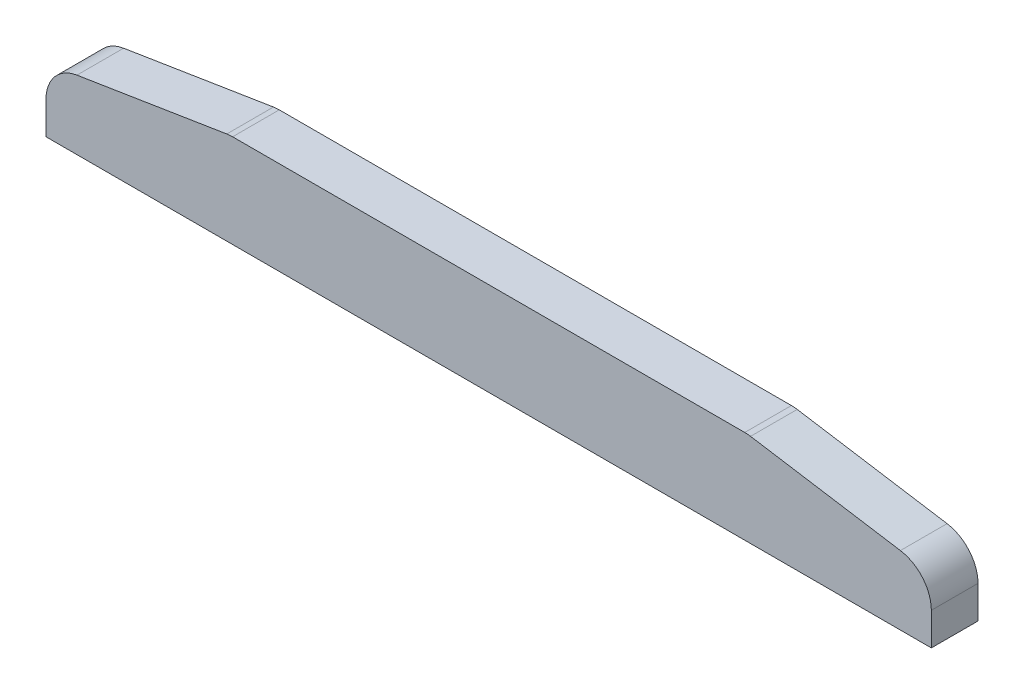
SolidWorks part; units mm, degrees
ref_plane "Front Plane" through (0, 0, 0) normal (0, 0, 1) x (1, 0, 0)
ref_plane "Top Plane" through (0, 0, 0) normal (0, 1, 0) x (1, 0, 0)
ref_plane "Right Plane" through (0, 0, 0) normal (1, 0, 0) x (0, 0, -1)
sketch "Sketch1" plane through (0, 0, 0) normal (0, 1, 0) x (1, 0, 0)
  line L1 (-120.5, -6.35) -> (120.5, -6.35)
  line L2 (-120.5, -6.35) -> (-120.5, 6.35)
  line L3 (-120.5, 6.35) -> (120.5, 6.35)
  line L4 (120.5, -6.35) -> (120.5, 6.35)
  line L5 (0, 6.35) -> (0, -6.35) construction
  line L6 (-120.5, 0) -> (120.5, 0) construction
  circle A0 centre (-112.5, 0) radius 2.1 construction
  circle A1 centre (-67.5, 0) radius 2.1 construction
  circle A2 centre (-22.5, 0) radius 2.1 construction
  circle A3 centre (22.5, 0) radius 2.1 construction
  circle A4 centre (67.5, 0) radius 2.1 construction
  circle A5 centre (112.5, 0) radius 2.1 construction
  point P0 (0, 0)
  dimension "D1" = 12.7
  dimension "D2" = 4.2
  dimension "D3" = 8
  dimension "D5" = 45
  dimension "D6" = 8
  dimension "D4" = 6
extrude "Boss-Extrude1" add sketch "Sketch1" along normal blind 25.4
chamfer "Chamfer1" distance 8 distance2 50 2 edges at (120.5, 25.4, 0) (-120.5, 25.4, 0)
hole_wizard "M5x0.8 Tapped Hole1" positions "Sketch2" profile "Sketch3" tap size "M5x0.8" standard "ANSI Metric"
sketch "Sketch2" plane through (0, 0, 0) normal (0, -1, 0) x (-1, 0, 0)
  point P15 (112.5, 0)
  point P18 (67.5, 0)
  point P21 (22.5, 0)
  point P24 (-22.5, 0)
  point P27 (-67.5, 0)
  point P30 (-112.5, 0)
sketch "Sketch3" plane through (-112.5, 0, 0) normal (1, 0, 0) x (0, 0, -1)
  line L0 (0, 0) -> (0, 13.2618)
  line L1 (0, 13.2618) -> (2.1, 12)
  line L2 (2.1, 12) -> (2.1, 0)
  line L5 (2.1, 0) -> (0, 0)
  line L10 (0, 13.2618) -> (-2.1, 12) construction
  line L11 (0, -6.35) -> (0, 107.95) construction
  dimension "Tap Drill Dia." = 4.2
  dimension "Tap Drill Depth" = 12
  dimension "Drill Angle" = 118
cosmetic thread "Hole Thread1"
cosmetic thread "Hole Thread2"
cosmetic thread "Hole Thread3"
cosmetic thread "Hole Thread4"
cosmetic thread "Hole Thread5"
cosmetic thread "Hole Thread6"
fillet "Fillet1" radius 10 4 edges at (120.5, 17.4, 0) (70.5, 25.4, 0) (-70.5, 25.4, 0) (-120.5, 17.4, 0)
